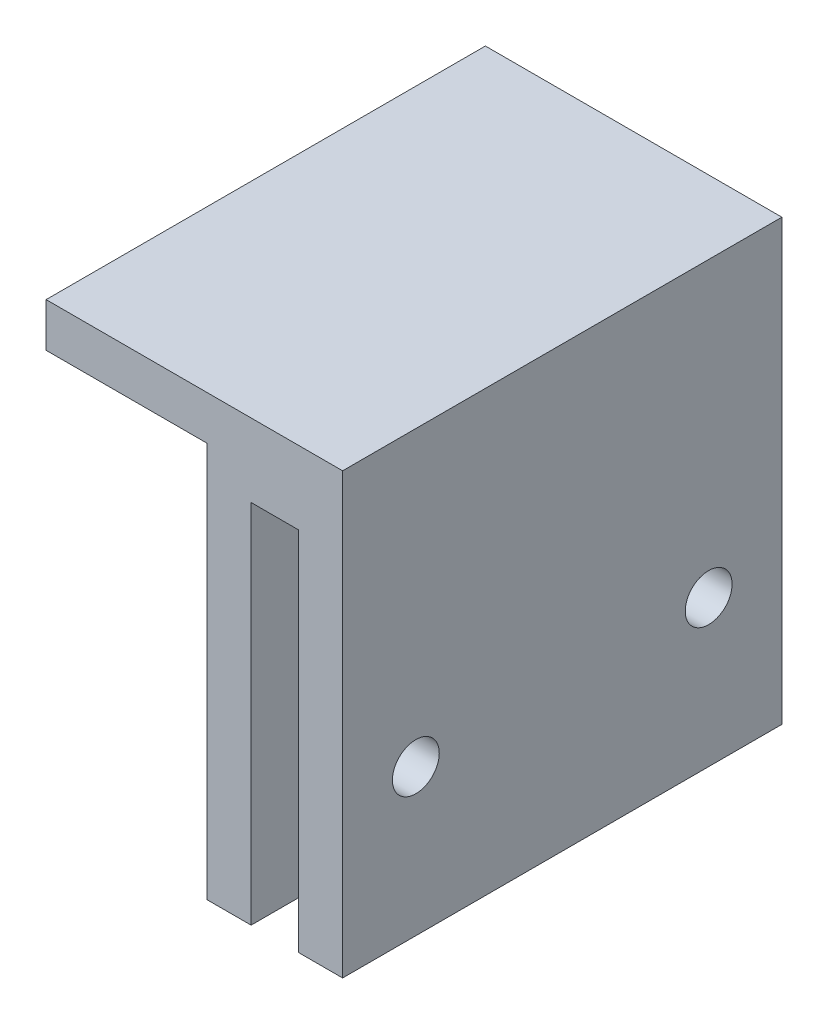
SolidWorks part; units mm, degrees
ref_plane "Front Plane" through (0, 0, 0) normal (0, 0, 1) x (1, 0, 0)
ref_plane "Top Plane" through (0, 0, 0) normal (0, 1, 0) x (1, 0, 0)
ref_plane "Right Plane" through (0, 0, 0) normal (1, 0, 0) x (0, 0, -1)
sketch "Sketch2" plane through (0, 0, 0) normal (1, 0, 0) x (0, 0, -1)
  line L0 (0, 0) -> (30, 0)
  line L1 (30, 0) -> (30, 30)
  line L2 (30, 30) -> (0, 30)
  line L3 (0, 30) -> (0, 0)
  line L4 (5, 10) -> (25, 10) construction
  circle A0 centre (5, 10) radius 1.6
  circle A1 centre (25, 10) radius 1.6
  point P9 (15, 0)
  point P10 (15, 10)
  dimension "D3" = 3.2
  dimension "D4" = 3.2
  dimension "D1" = 30
  dimension "D2" = 30
  dimension "D5" = 10
  dimension "D6" = 20
extrude "Boss-Extrude1" add sketch "Sketch2" against normal blind 9.25
sketch "Sketch3" plane through (0, 0, 0) normal (0, 0, 1) x (1, 0, 0)
  line L0 (-6.25, 0) -> (-6.25, 25)
  line L1 (-9.25, 0) -> (0, 0) construction
  line L2 (-6.25, 25) -> (-3, 25)
  line L3 (-3, 25) -> (-3, 0)
  line L4 (-3, 0) -> (-6.25, 0)
  line L5 (0, 30) -> (0, 0) construction
  dimension "D1" = 3.25
  dimension "D2" = 25
  dimension "D3" = 3
extrude "Cut-Extrude1" cut sketch "Sketch3" against normal through all
sketch "Sketch5" plane through (-9.25, 0, 0) normal (-1, 0, 0) x (0, 0, 1)
  line L0 (-30, 30) -> (-30, 27)
  line L1 (-30, 0) -> (-30, 30) construction
  line L2 (-30, 27) -> (0, 27)
  line L3 (0, 30) -> (0, 0) construction
  line L4 (0, 27) -> (0, 30)
  line L5 (0, 30) -> (-30, 30)
  line L6 (-30, 30) -> (0, 30) construction
  dimension "D1" = 3
extrude "Boss-Extrude2" add sketch "Sketch5" along normal blind 11
